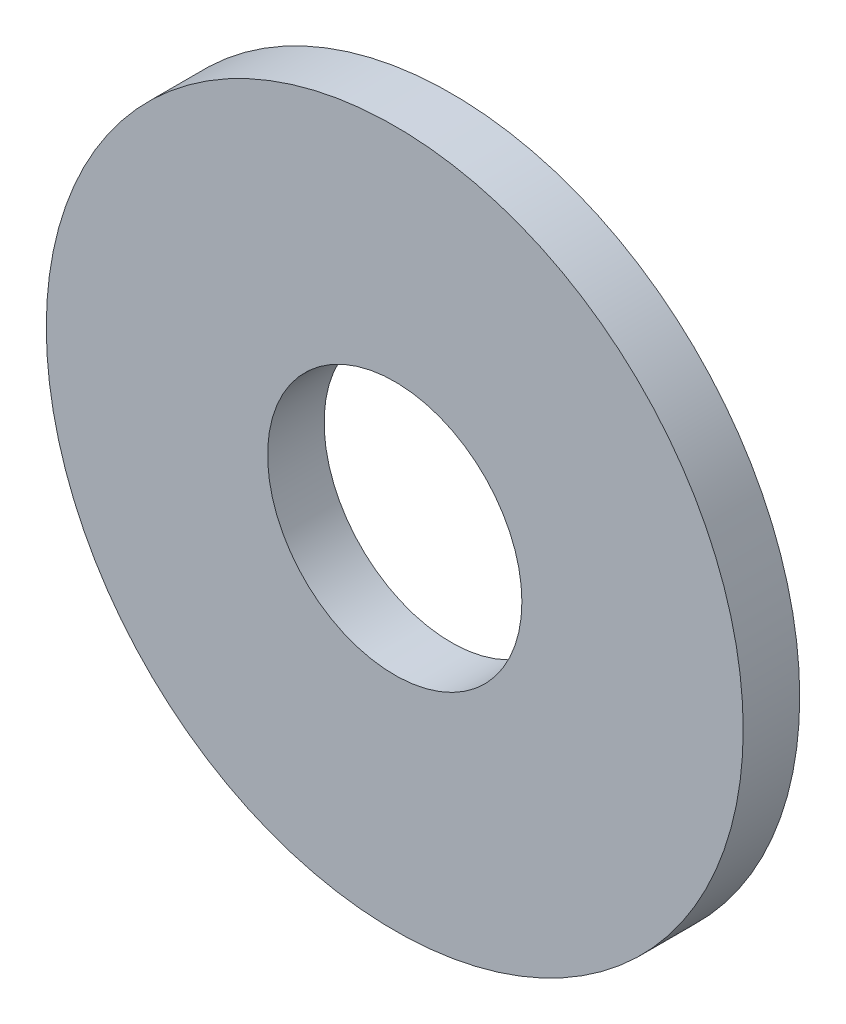
SolidWorks part; units mm, degrees
ref_plane "Front Plane" through (0, 0, 0) normal (0, 0, 1) x (1, 0, 0)
ref_plane "Top Plane" through (0, 0, 0) normal (0, 1, 0) x (1, 0, 0)
ref_plane "Right Plane" through (0, 0, 0) normal (1, 0, 0) x (0, 0, -1)
sketch "Sketch1" plane through (0, 0, 0) normal (0, 0, 1) x (1, 0, 0)
  circle A0 centre (0, 0) radius 7.4 construction
  circle A1 centre (0, 0) radius 2.7 construction
  point P5 (-2.7, 0)
  point P6 (2.7, 0)
  point P7 (7.4, 0)
  point P8 (-7.4, 0)
  dimension "OD" = 14.8
  dimension "ID" = 5.4
sketch "Sketch2" plane through (0, 0, 0) normal (1, 0, 0) x (0, 0, -1)
  line L0 (0.6, 0) -> (-0.6, 0) construction
  line L1 (0, 7.4) -> (0, -7.4) construction
  line L2 (0, 7.4) -> (0, -7.4) construction
  line L3 (0.6, 7.4) -> (-0.6, 7.4) construction
  line L4 (0.6, -7.4) -> (-0.6, -7.4) construction
  line L5 (-0.6, -7.4) -> (-0.6, 7.4) construction
  line L6 (0.6, -7.4) -> (0.6, 7.4) construction
  point P4 (0, 0)
  point P10 (0, 7.4)
  point P11 (-0.6, 7.4)
  point P14 (0, -7.4)
  point P15 (-0.6, -7.4)
  point P16 (0.6, -7.4)
  point P17 (0.6, 7.4)
  point P18 (0.6, 0)
  point P19 (-0.6, 0)
  dimension "Thickness" = 1.2
sketch "Sketch3" plane through (0, 0, 0) normal (0, 0, 1) x (1, 0, 0)
  circle A0 centre (0, 0) radius 7.4 construction
  circle A1 centre (0, 0) radius 2.7 construction
  circle A2 centre (0, 0) radius 7.4
  circle A3 centre (0, 0) radius 2.7
extrude "Boss-Extrude1" add sketch "Sketch3" along normal mid plane 1.2
equation "\"D1@Boss-Extrude1\"=\"Thickness@Sketch2\""
